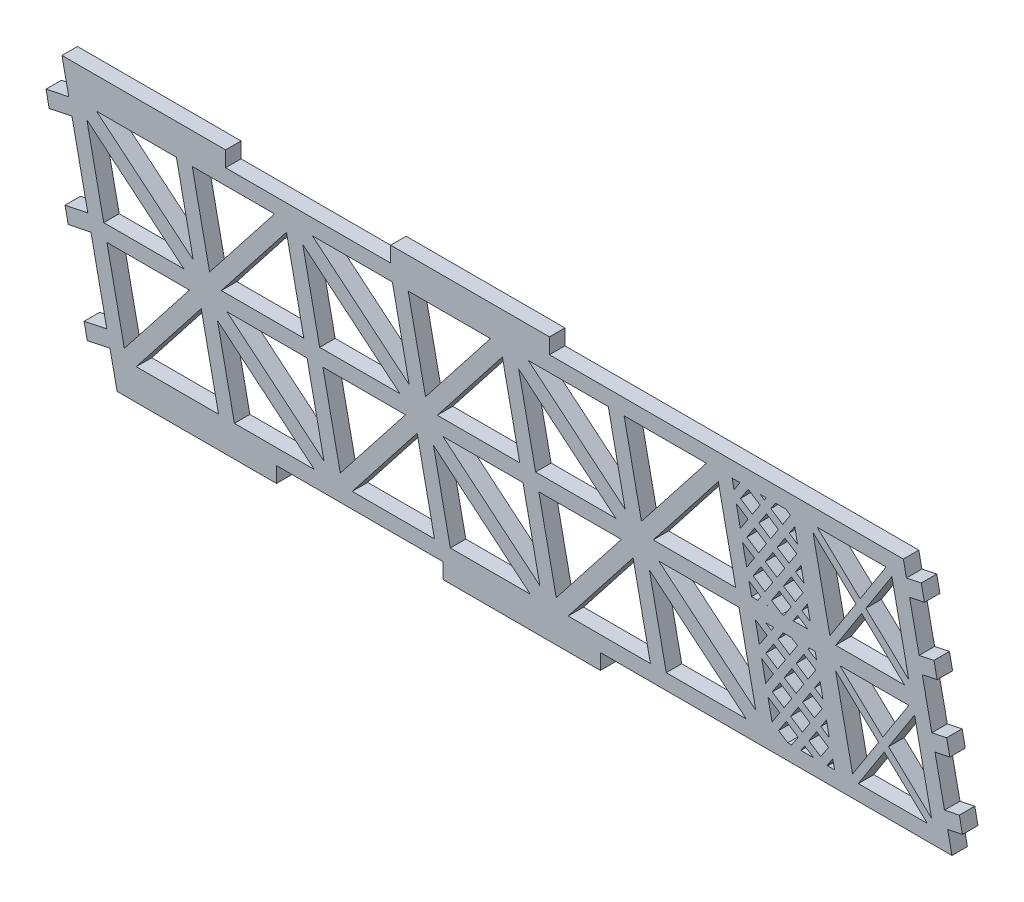
SolidWorks part; units mm, degrees
ref_plane "Front Plane" through (0, 0, 0) normal (0, 0, 1) x (1, 0, 0)
ref_plane "Top Plane" through (0, 0, 0) normal (0, 1, 0) x (1, 0, 0)
ref_plane "Right Plane" through (0, 0, 0) normal (1, 0, 0) x (0, 0, -1)
sketch "Sketch1" plane through (0, 0, 0) normal (0, 0, 1) x (1, 0, 0)
  line L3058 (423.3082, 291) -> (421.7679, 291)
  line L3059 (421.7679, 291) -> (422.1411, 289.2157)
  line L3060 (422.1411, 289.2157) -> (423.3082, 291)
  line L3061 (427.193, 289.1887) -> (425.6918, 286.8934)
  line L3062 (425.6918, 286.8934) -> (423.3965, 288.3946)
  line L3063 (423.3965, 288.3946) -> (424.8977, 290.6899)
  line L3064 (424.8977, 290.6899) -> (427.193, 289.1887)
  line L3065 (422.5754, 287.1393) -> (423.3695, 283.3427)
  line L3066 (423.3695, 283.3427) -> (424.8707, 285.638)
  line L3067 (424.8707, 285.638) -> (422.5754, 287.1393)
  line L3068 (428.3777, 291) -> (427.164, 291)
  line L3069 (427.164, 291) -> (428.0141, 290.444)
  line L3070 (428.0141, 290.444) -> (428.3777, 291)
  line L3071 (432.1745, 291) -> (433.0659, 290.417)
  line L3072 (433.0659, 290.417) -> (431.5647, 288.1217)
  line L3073 (431.5647, 288.1217) -> (429.2694, 289.6229)
  line L3074 (429.2694, 289.6229) -> (430.1701, 291)
  line L3075 (430.1701, 291) -> (432.1745, 291)
  line L3076 (430.7436, 286.8664) -> (429.2424, 284.5711)
  line L3077 (429.2424, 284.5711) -> (426.9471, 286.0723)
  line L3078 (426.9471, 286.0723) -> (428.4483, 288.3676)
  line L3079 (428.4483, 288.3676) -> (430.7436, 286.8664)
  line L3080 (428.4213, 283.3157) -> (426.9201, 281.0204)
  line L3081 (426.9201, 281.0204) -> (424.6248, 282.5217)
  line L3082 (424.6248, 282.5217) -> (426.126, 284.817)
  line L3083 (426.126, 284.817) -> (428.4213, 283.3157)
  line L3084 (423.8037, 281.2663) -> (424.5978, 277.4698)
  line L3085 (424.5978, 277.4698) -> (426.099, 279.7651)
  line L3086 (426.099, 279.7651) -> (423.8037, 281.2663)
  line L3087 (434.4489, 286.2353) -> (432.82, 287.3006)
  line L3088 (432.82, 287.3006) -> (433.8854, 288.9295)
  line L3089 (433.8854, 288.9295) -> (434.4489, 286.2353)
  line L3090 (434.2942, 284.5441) -> (432.793, 282.2488)
  line L3091 (432.793, 282.2488) -> (430.4977, 283.75)
  line L3092 (430.4977, 283.75) -> (431.999, 286.0453)
  line L3093 (431.999, 286.0453) -> (434.2942, 284.5441)
  line L3094 (431.972, 280.9934) -> (430.4707, 278.6981)
  line L3095 (430.4707, 278.6981) -> (428.1754, 280.1994)
  line L3096 (428.1754, 280.1994) -> (429.6767, 282.4947)
  line L3097 (429.6767, 282.4947) -> (431.972, 280.9934)
  line L3098 (429.6497, 277.4428) -> (428.1484, 275.1475)
  line L3099 (428.1484, 275.1475) -> (425.8531, 276.6488)
  line L3100 (425.8531, 276.6488) -> (427.3544, 278.9441)
  line L3101 (427.3544, 278.9441) -> (429.6497, 277.4428)
  line L3102 (425.0321, 275.3934) -> (425.5327, 273)
  line L3103 (425.5327, 273) -> (426.7438, 273)
  line L3104 (426.7438, 273) -> (427.3274, 273.8922)
  line L3105 (427.3274, 273.8922) -> (425.0321, 275.3934)
  line L3106 (435.6772, 280.3623) -> (434.0483, 281.4277)
  line L3107 (434.0483, 281.4277) -> (435.1137, 283.0566)
  line L3108 (435.1137, 283.0566) -> (435.6772, 280.3623)
  line L3109 (435.5226, 278.6711) -> (434.0213, 276.3758)
  line L3110 (434.0213, 276.3758) -> (431.726, 277.8771)
  line L3111 (431.726, 277.8771) -> (433.2273, 280.1724)
  line L3112 (433.2273, 280.1724) -> (435.5226, 278.6711)
  line L3113 (433.2003, 275.1205) -> (431.8134, 273)
  line L3114 (431.8134, 273) -> (431.4318, 273)
  line L3115 (431.4318, 273) -> (429.4037, 274.3265)
  line L3116 (429.4037, 274.3265) -> (430.905, 276.6218)
  line L3117 (430.905, 276.6218) -> (433.2003, 275.1205)
  line L3118 (428.6914, 273) -> (428.5362, 273)
  line L3119 (428.5362, 273) -> (428.5827, 273.0711)
  line L3120 (428.5827, 273.0711) -> (428.6914, 273)
  line L3121 (426.2604, 269.5205) -> (427.0544, 265.724)
  line L3122 (427.0544, 265.724) -> (428.5557, 268.0193)
  line L3123 (428.5557, 268.0193) -> (426.2604, 269.5205)
  line L3124 (436.9056, 274.4894) -> (435.2767, 275.5548)
  line L3125 (435.2767, 275.5548) -> (436.342, 277.1837)
  line L3126 (436.342, 277.1837) -> (436.9056, 274.4894)
  line L3127 (436.4424, 273) -> (433.6057, 273)
  line L3128 (433.6057, 273) -> (434.4556, 274.2995)
  line L3129 (434.4556, 274.2995) -> (436.4424, 273)
  line L3130 (433.2782, 270) -> (434.4286, 269.2476)
  line L3131 (434.4286, 269.2476) -> (432.9274, 266.9523)
  line L3132 (432.9274, 266.9523) -> (430.6321, 268.4535)
  line L3133 (430.6321, 268.4535) -> (431.6435, 270)
  line L3134 (431.6435, 270) -> (433.2782, 270)
  line L3135 (432.1063, 265.697) -> (430.6051, 263.4017)
  line L3136 (430.6051, 263.4017) -> (428.3098, 264.9029)
  line L3137 (428.3098, 264.9029) -> (429.811, 267.1982)
  line L3138 (429.811, 267.1982) -> (432.1063, 265.697)
  line L3139 (427.4887, 263.6476) -> (428.2828, 259.8511)
  line L3140 (428.2828, 259.8511) -> (429.784, 262.1463)
  line L3141 (429.784, 262.1463) -> (427.4887, 263.6476)
  line L3142 (428.2677, 270) -> (429.8512, 270)
  line L3143 (429.8512, 270) -> (429.3767, 269.2746)
  line L3144 (429.3767, 269.2746) -> (428.2677, 270)
  line L3145 (437.8445, 270) -> (438.1339, 268.6165)
  line L3146 (438.1339, 268.6165) -> (436.505, 269.6819)
  line L3147 (436.505, 269.6819) -> (436.7131, 270)
  line L3148 (436.7131, 270) -> (437.8445, 270)
  line L3149 (437.9792, 266.9253) -> (436.478, 264.63)
  line L3150 (436.478, 264.63) -> (434.1827, 266.1312)
  line L3151 (434.1827, 266.1312) -> (435.6839, 268.4265)
  line L3152 (435.6839, 268.4265) -> (437.9792, 266.9253)
  line L3153 (435.6569, 263.3747) -> (434.1557, 261.0794)
  line L3154 (434.1557, 261.0794) -> (431.8604, 262.5806)
  line L3155 (431.8604, 262.5806) -> (433.3616, 264.8759)
  line L3156 (433.3616, 264.8759) -> (435.6569, 263.3747)
  line L3157 (433.3346, 259.824) -> (431.8334, 257.5288)
  line L3158 (431.8334, 257.5288) -> (429.5381, 259.03)
  line L3159 (429.5381, 259.03) -> (431.0393, 261.3253)
  line L3160 (431.0393, 261.3253) -> (433.3346, 259.824)
  line L3161 (428.7171, 257.7747) -> (429.5111, 253.9781)
  line L3162 (429.5111, 253.9781) -> (431.0123, 256.2734)
  line L3163 (431.0123, 256.2734) -> (428.7171, 257.7747)
  line L3164 (439.3622, 262.7436) -> (437.7333, 263.809)
  line L3165 (437.7333, 263.809) -> (438.7987, 265.4378)
  line L3166 (438.7987, 265.4378) -> (439.3622, 262.7436)
  line L3167 (439.2076, 261.0524) -> (437.7063, 258.7571)
  line L3168 (437.7063, 258.7571) -> (435.411, 260.2583)
  line L3169 (435.411, 260.2583) -> (436.9123, 262.5536)
  line L3170 (436.9123, 262.5536) -> (439.2076, 261.0524)
  line L3171 (436.8853, 257.5017) -> (435.384, 255.2065)
  line L3172 (435.384, 255.2065) -> (433.0887, 256.7077)
  line L3173 (433.0887, 256.7077) -> (434.59, 259.003)
  line L3174 (434.59, 259.003) -> (436.8853, 257.5017)
  line L3175 (434.563, 253.9511) -> (433.2868, 252)
  line L3176 (433.2868, 252) -> (432.5355, 252)
  line L3177 (432.5355, 252) -> (430.7664, 253.1571)
  line L3178 (430.7664, 253.1571) -> (432.2677, 255.4524)
  line L3179 (432.2677, 255.4524) -> (434.563, 253.9511)
  line L3180 (440.5905, 256.8706) -> (438.9617, 257.936)
  line L3181 (438.9617, 257.936) -> (440.027, 259.5649)
  line L3182 (440.027, 259.5649) -> (440.5905, 256.8706)
  line L3183 (440.4359, 255.1795) -> (438.9346, 252.8842)
  line L3184 (438.9346, 252.8842) -> (436.6394, 254.3854)
  line L3185 (436.6394, 254.3854) -> (438.1406, 256.6807)
  line L3186 (438.1406, 256.6807) -> (440.4359, 255.1795)
  line L3187 (437.5461, 252) -> (435.0792, 252)
  line L3188 (435.0792, 252) -> (435.8183, 253.1301)
  line L3189 (435.8183, 253.1301) -> (437.5461, 252)
  line L3190 (441.6092, 252) -> (440.2865, 252)
  line L3191 (440.2865, 252) -> (440.19, 252.0631)
  line L3192 (440.19, 252.0631) -> (441.2554, 253.692)
  line L3193 (441.2554, 253.692) -> (441.6092, 252)
  line L3194 (460.374, 253.2841) -> (452.0654, 261.1186)
  line L3195 (452.0654, 261.1186) -> (457.0969, 268.953)
  line L3196 (457.0969, 268.953) -> (460.374, 253.2841)
  line L3197 (459.5494, 252) -> (446.2094, 252)
  line L3198 (446.2094, 252) -> (451.2408, 259.8345)
  line L3199 (451.2408, 259.8345) -> (459.5494, 252)
  line L3200 (441.8219, 268.7159) -> (450.1305, 260.8814)
  line L3201 (450.1305, 260.8814) -> (445.0991, 253.047)
  line L3202 (445.0991, 253.047) -> (441.8219, 268.7159)
  line L3203 (442.6465, 270) -> (455.9865, 270)
  line L3204 (455.9865, 270) -> (450.9551, 262.1655)
  line L3205 (450.9551, 262.1655) -> (442.6465, 270)
  line L3206 (455.9819, 274.2841) -> (447.6733, 282.1186)
  line L3207 (447.6733, 282.1186) -> (452.7047, 289.953)
  line L3208 (452.7047, 289.953) -> (455.9819, 274.2841)
  line L3209 (437.4297, 289.7159) -> (445.7383, 281.8814)
  line L3210 (445.7383, 281.8814) -> (440.7069, 274.047)
  line L3211 (440.7069, 274.047) -> (437.4297, 289.7159)
  line L3212 (451.5944, 291) -> (438.2544, 291)
  line L3213 (438.2544, 291) -> (446.563, 283.1655)
  line L3214 (446.563, 283.1655) -> (451.5944, 291)
  line L3215 (455.1572, 273) -> (441.8172, 273)
  line L3216 (441.8172, 273) -> (446.8486, 280.8345)
  line L3217 (446.8486, 280.8345) -> (455.1572, 273)
  line L3218 (400.8658, 291) -> (416.7968, 291)
  line L3219 (416.7968, 291) -> (404.2202, 274.9618)
  line L3220 (404.2202, 274.9618) -> (400.8658, 291)
  line L3221 (422.4677, 273) -> (406.4943, 273)
  line L3222 (406.4943, 273) -> (419.1044, 289.081)
  line L3223 (419.1044, 289.081) -> (422.4677, 273)
  line L3224 (390.0268, 252) -> (405.9578, 252)
  line L3225 (405.9578, 252) -> (402.6034, 268.0382)
  line L3226 (402.6034, 268.0382) -> (390.0268, 252)
  line L3227 (384.3559, 270) -> (400.3294, 270)
  line L3228 (400.3294, 270) -> (387.7193, 253.919)
  line L3229 (387.7193, 253.919) -> (384.3559, 270)
  line L3230 (359.0616, 291) -> (374.9926, 291)
  line L3231 (374.9926, 291) -> (362.416, 274.9618)
  line L3232 (362.416, 274.9618) -> (359.0616, 291)
  line L3233 (380.6635, 273) -> (364.6901, 273)
  line L3234 (364.6901, 273) -> (377.3002, 289.081)
  line L3235 (377.3002, 289.081) -> (380.6635, 273)
  line L3236 (348.2226, 252) -> (364.1536, 252)
  line L3237 (364.1536, 252) -> (360.7992, 268.0382)
  line L3238 (360.7992, 268.0382) -> (348.2226, 252)
  line L3239 (342.5517, 270) -> (358.5252, 270)
  line L3240 (358.5252, 270) -> (345.9151, 253.919)
  line L3241 (345.9151, 253.919) -> (342.5517, 270)
  line L3242 (317.2574, 291) -> (333.1884, 291)
  line L3243 (333.1884, 291) -> (320.6118, 274.9618)
  line L3244 (320.6118, 274.9618) -> (317.2574, 291)
  line L3245 (338.8593, 273) -> (322.8859, 273)
  line L3246 (322.8859, 273) -> (335.496, 289.081)
  line L3247 (335.496, 289.081) -> (338.8593, 273)
  line L3248 (322.3494, 252) -> (306.4184, 252)
  line L3249 (306.4184, 252) -> (318.995, 268.0382)
  line L3250 (318.995, 268.0382) -> (322.3494, 252)
  line L3251 (300.7475, 270) -> (316.721, 270)
  line L3252 (316.721, 270) -> (304.1109, 253.919)
  line L3253 (304.1109, 253.919) -> (300.7475, 270)
  line L3254 (296.8493, 288.6383) -> (300.1201, 273)
  line L3255 (300.1201, 273) -> (315.6538, 273)
  line L3256 (315.6538, 273) -> (296.8493, 288.6383)
  line L3257 (298.7013, 291) -> (314.1925, 291)
  line L3258 (314.1925, 291) -> (317.4543, 275.4045)
  line L3259 (317.4543, 275.4045) -> (298.7013, 291)
  line L3260 (325.4143, 252) -> (322.1525, 267.5955)
  line L3261 (322.1525, 267.5955) -> (340.9056, 252)
  line L3262 (340.9056, 252) -> (325.4143, 252)
  line L3263 (339.4868, 270) -> (342.7576, 254.3617)
  line L3264 (342.7576, 254.3617) -> (323.953, 270)
  line L3265 (323.953, 270) -> (339.4868, 270)
  line L3266 (357.458, 273) -> (341.9243, 273)
  line L3267 (341.9243, 273) -> (338.6535, 288.6383)
  line L3268 (338.6535, 288.6383) -> (357.458, 273)
  line L3269 (340.5055, 291) -> (355.9967, 291)
  line L3270 (355.9967, 291) -> (359.2585, 275.4045)
  line L3271 (359.2585, 275.4045) -> (340.5055, 291)
  line L3272 (367.2185, 252) -> (363.9567, 267.5955)
  line L3273 (363.9567, 267.5955) -> (382.7098, 252)
  line L3274 (382.7098, 252) -> (367.2185, 252)
  line L3275 (381.291, 270) -> (384.5618, 254.3617)
  line L3276 (384.5618, 254.3617) -> (365.7572, 270)
  line L3277 (365.7572, 270) -> (381.291, 270)
  line L3278 (399.2622, 273) -> (383.7285, 273)
  line L3279 (383.7285, 273) -> (380.4577, 288.6383)
  line L3280 (380.4577, 288.6383) -> (399.2622, 273)
  line L3281 (382.3097, 291) -> (397.8009, 291)
  line L3282 (397.8009, 291) -> (401.0627, 275.4045)
  line L3283 (401.0627, 275.4045) -> (382.3097, 291)
  line L3284 (409.0227, 252) -> (405.7609, 267.5955)
  line L3285 (405.7609, 267.5955) -> (424.514, 252)
  line L3286 (424.514, 252) -> (409.0227, 252)
  line L3287 (423.0952, 270) -> (426.366, 254.3617)
  line L3288 (426.366, 254.3617) -> (407.5614, 270)
  line L3289 (407.5614, 270) -> (423.0952, 270)
  line L3290 (302.7022, 246) -> (333.5748, 246)
  line L3291 (333.5748, 246) -> (333.5748, 249)
  line L3292 (333.5748, 249) -> (365.8248, 249)
  line L3293 (365.8248, 249) -> (365.8248, 246)
  line L3294 (365.8248, 246) -> (396.2748, 246)
  line L3295 (396.2748, 246) -> (396.2748, 249)
  line L3296 (396.2748, 249) -> (464.335, 249)
  line L3297 (464.335, 249) -> (463.5082, 252.9531)
  line L3298 (463.5082, 252.9531) -> (466.3789, 253.5535)
  line L3299 (466.3789, 253.5535) -> (465.7647, 256.49)
  line L3300 (465.7647, 256.49) -> (462.894, 255.8895)
  line L3301 (462.894, 255.8895) -> (461.0515, 264.6989)
  line L3302 (461.0515, 264.6989) -> (463.9222, 265.2993)
  line L3303 (463.9222, 265.2993) -> (463.3081, 268.2358)
  line L3304 (463.3081, 268.2358) -> (460.4374, 267.6354)
  line L3305 (460.4374, 267.6354) -> (458.5949, 276.4448)
  line L3306 (458.5949, 276.4448) -> (461.4656, 277.0452)
  line L3307 (461.4656, 277.0452) -> (460.8514, 279.9816)
  line L3308 (460.8514, 279.9816) -> (457.9807, 279.3812)
  line L3309 (457.9807, 279.3812) -> (456.1382, 288.1906)
  line L3310 (456.1382, 288.1906) -> (459.0089, 288.791)
  line L3311 (459.0089, 288.791) -> (458.3947, 291.7275)
  line L3312 (458.3947, 291.7275) -> (455.524, 291.1271)
  line L3313 (455.524, 291.1271) -> (454.9232, 294)
  line L3314 (454.9232, 294) -> (386.413, 294)
  line L3315 (386.413, 294) -> (386.413, 297)
  line L3316 (386.413, 297) -> (355.663, 297)
  line L3317 (355.663, 297) -> (355.663, 294)
  line L3318 (355.663, 294) -> (323.713, 294)
  line L3319 (323.713, 294) -> (323.713, 297)
  line L3320 (323.713, 297) -> (292.0355, 297)
  line L3321 (292.0355, 297) -> (293.3483, 290.7233)
  line L3322 (293.3483, 290.7233) -> (288.9436, 289.8021)
  line L3323 (288.9436, 289.8021) -> (289.5578, 286.8656)
  line L3324 (289.5578, 286.8656) -> (293.9625, 287.7869)
  line L3325 (293.9625, 287.7869) -> (297.0333, 273.1045)
  line L3326 (297.0333, 273.1045) -> (292.6286, 272.1833)
  line L3327 (292.6286, 272.1833) -> (293.2428, 269.2468)
  line L3328 (293.2428, 269.2468) -> (297.6474, 270.1681)
  line L3329 (297.6474, 270.1681) -> (300.7183, 255.4858)
  line L3330 (300.7183, 255.4858) -> (296.3136, 254.5645)
  line L3331 (296.3136, 254.5645) -> (296.9277, 251.6281)
  line L3332 (296.9277, 251.6281) -> (301.3324, 252.5493)
  line L3333 (301.3324, 252.5493) -> (302.7022, 246)
extrude "Boss-Extrude1" add sketch "Sketch1" along normal blind 3
